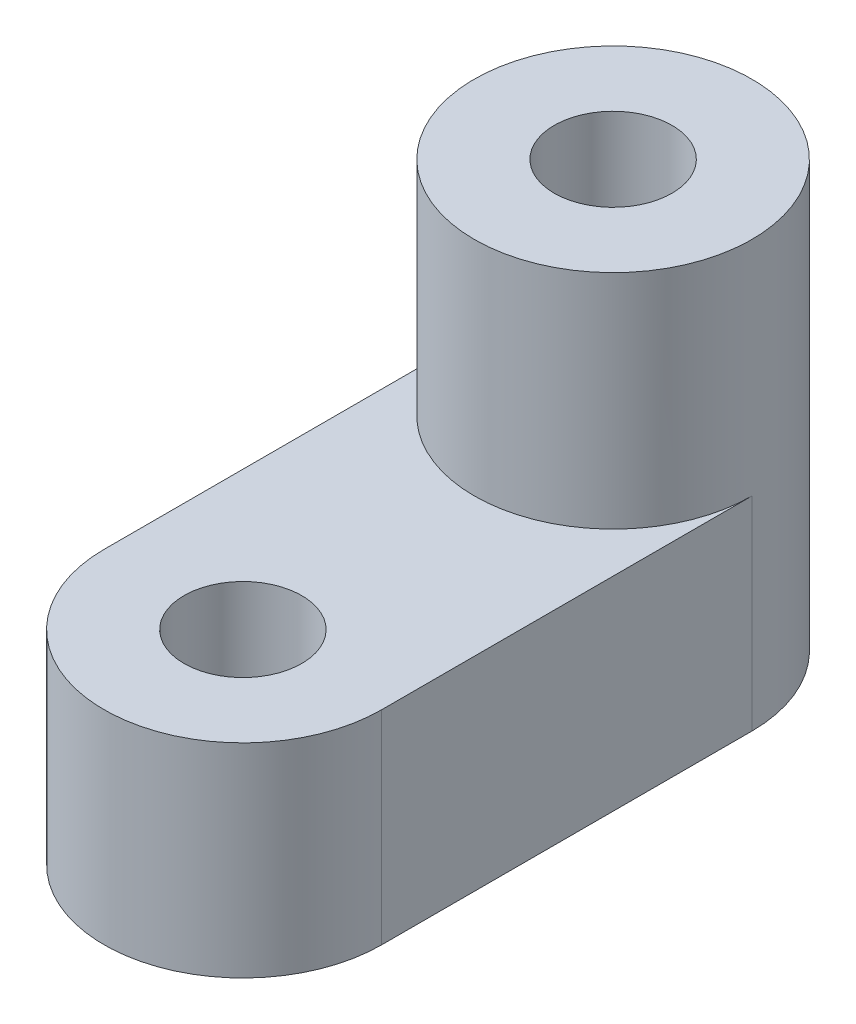
SolidWorks part; units mm, degrees
ref_plane "Front Plane" through (0, 0, 0) normal (0, 0, 1) x (1, 0, 0)
ref_plane "Top Plane" through (0, 0, 0) normal (0, 1, 0) x (1, 0, 0)
ref_plane "Right Plane" through (0, 0, 0) normal (1, 0, 0) x (0, 0, -1)
sketch "Sketch1" plane through (0, 0, 0) normal (0, 1, 0) x (1, 0, 0)
  line L2 (-3.75, 0) -> (-3.75, 10)
  line L3 (-3.75, 10) -> (3.75, 10)
  line L4 (3.75, 0) -> (3.75, 10)
  circle A0 centre (0, 0) radius 3.75
  point P0 (0, 0)
  dimension "D3" = 7.5
  dimension "D1" = 10
  dimension "D2" = 3.75
extrude "Boss-Extrude1" add sketch "Sketch1" along normal blind 5.5 contours A0 L4 L3 L2
sketch "Sketch2" plane through (0, 5.5, 0) normal (0, 1, 0) x (1, 0, 0)
  circle A0 centre (0, 0) radius 1.59
extrude "Cut-Extrude1" cut sketch "Sketch2" against normal through all
sketch "Sketch3" plane through (0, 5.5, 0) normal (0, 1, 0) x (1, 0, 0)
  line L0 (-3.75, 0) -> (-3.75, 10) construction
  circle A0 centre (0, 10) radius 3.75
  dimension "D2" = 7.5
  dimension "D1" = 10
  dimension "D3" = 3.75
extrude "Boss-Extrude2" add sketch "Sketch3" along normal blind 6 and the other way up to surface other way up to face at (0, 0, 1.59)
sketch "Sketch4" plane through (0, 11.5, 0) normal (0, 1, 0) x (1, 0, 0)
  circle A0 centre (0, 10) radius 1.59
extrude "Cut-Extrude2" cut sketch "Sketch4" against normal blind 10
sketch "Sketch6" plane through (0, 5.5, 0) normal (0, 1, 0) x (1, 0, 0)
sketch "Sketch7" plane through (-3.75, 0, 0) normal (-1, 0, 0) x (0, 0, 1)
  line L0 (-10.1052, 5.5) -> (-10.1052, 0)
  line L1 (0, 5.5) -> (-10, 5.5) construction
  line L2 (0, 0) -> (-10, 0) construction
sketch "Sketch8" plane through (3.75, 0, 0) normal (1, 0, 0) x (0, 0, -1)
  line L0 (9.8459, 5.5) -> (9.8459, 0)
  line L1 (0, 5.5) -> (10, 5.5) construction
  line L2 (0, 0) -> (10, 0) construction
